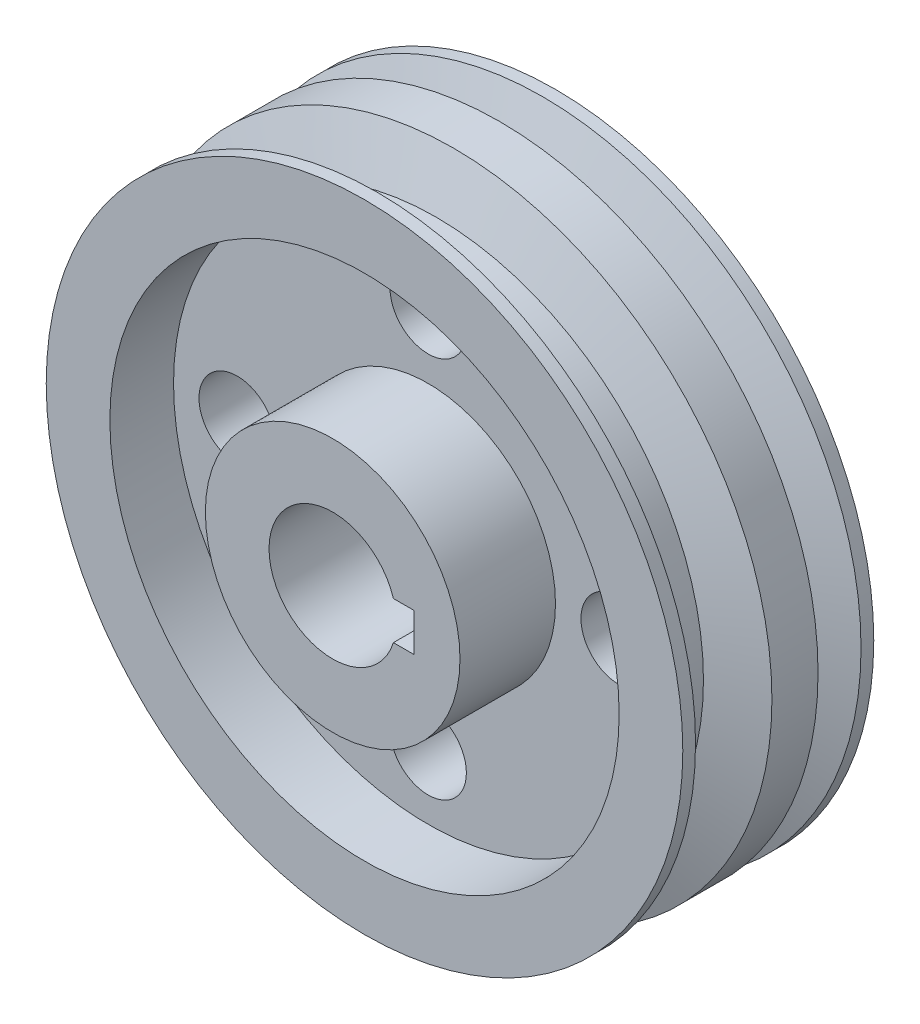
SolidWorks part; units mm, degrees
ref_plane "前视基准面" through (0, 0, 0) normal (0, 0, 1) x (1, 0, 0)
ref_plane "上视基准面" through (0, 0, 0) normal (0, 1, 0) x (1, 0, 0)
ref_plane "右视基准面" through (0, 0, 0) normal (1, 0, 0) x (0, 0, -1)
sketch "草图1" plane through (0, 0, 0) normal (0, 1, 0) x (1, 0, 0)
  line L0 (0, 20) -> (0, -20) construction
  line L1 (0, 20) -> (20, 20)
  line L2 (20, 20) -> (20, 5)
  line L3 (20, 5) -> (40, 5)
  line L4 (40, 5) -> (40, 15)
  line L5 (40, 15) -> (50, 15)
  line L6 (50, 15) -> (50, -15)
  line L7 (50, -15) -> (40, -15)
  line L8 (40, -15) -> (40, -5)
  line L9 (40, -5) -> (20, -5)
  line L10 (20, -5) -> (20, -20)
  line L11 (20, -20) -> (0, -20)
  line L12 (0, -20) -> (0, 20)
revolve "旋转1" add sketch "草图1" angle 360 about L0
sketch "草图2" plane through (0, 0, 0) normal (0, 1, 0) x (1, 0, 0)
  line L0 (0, 20) -> (0, -20) construction
  line L1 (42, -3.7546) -> (51, -0.6557)
  line L2 (51, -0.6557) -> (51, -13.3443)
  line L3 (51, -13.3443) -> (42, -10.2454)
  line L4 (42, -10.2454) -> (42, -3.7546)
  line L5 (42, 3.7546) -> (51, 6.5557)
  line L6 (51, 6.5557) -> (51, 13.3443)
  line L7 (51, 13.3443) -> (42, 10.2454)
  line L8 (42, 10.2454) -> (42, 3.7546)
revolve "切除-旋转1" cut sketch "草图2" angle 360 about L0
ref_plane "基准面1" through (0, 0, 20) normal (0, 0, 1) x (1, 0, 0)
sketch "草图3" plane through (0, 0, 20) normal (0, 0, 1) x (1, 0, 0)
  line L0 (0, -3) -> (12.8, -3)
  line L1 (12.8, -3) -> (12.8, 3)
  line L2 (12.8, 3) -> (0, 3)
  line L3 (0, 3) -> (0, -3)
extrude "切除-拉伸1" cut sketch "草图3" against normal through all
sketch "草图4" plane through (0, 0, 20) normal (0, 0, 1) x (1, 0, 0)
  circle A0 centre (30, 0) radius 6
  circle A1 centre (0, 30) radius 6
  circle A2 centre (-30, 0) radius 6
  circle A3 centre (0, -30) radius 6
extrude "切除-拉伸2" cut sketch "草图4" against normal through all
sketch "草图5" plane through (0, 0, 20) normal (0, 0, 1) x (1, 0, 0)
  circle A0 centre (0, 0) radius 10
extrude "切除-拉伸3" cut sketch "草图5" against normal mid plane 202
